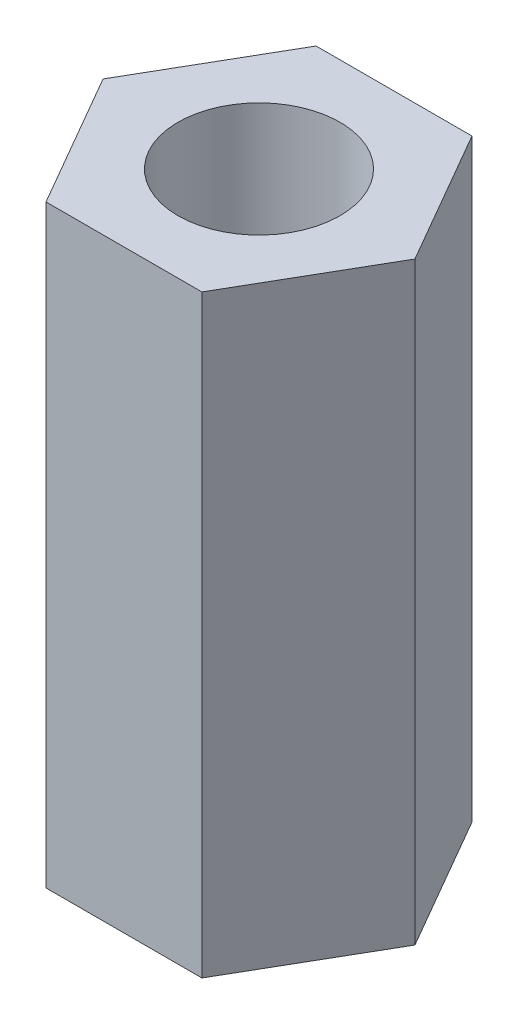
SolidWorks part; units mm, degrees
material "ABS"
ref_plane "Alzado" through (0, 0, 0) normal (0, 0, 1) x (1, 0, 0)
ref_plane "Planta" through (0, 0, 0) normal (0, 1, 0) x (1, 0, 0)
ref_plane "Vista lateral" through (0, 0, 0) normal (1, 0, 0) x (0, 0, -1)
sketch "Croquis1" plane through (0, 0, 0) normal (0, 1, 0) x (1, 0, 0)
  line L1 (1.4434, -2.5) -> (2.8868, 0)
  line L2 (2.8868, 0) -> (1.4434, 2.5)
  line L3 (1.4434, 2.5) -> (-1.4434, 2.5)
  line L4 (-1.4434, 2.5) -> (-2.8868, 0)
  line L5 (-2.8868, 0) -> (-1.4434, -2.5)
  line L6 (-1.4434, -2.5) -> (1.4434, -2.5)
  circle A0 centre (0, 0) radius 2.5 construction
  circle A1 centre (0, 0) radius 1.5
  dimension "D2" = 3
  dimension "D1" = 5
extrude "Saliente-Extruir1" add sketch "Croquis1" along normal mid plane 12
sketch "草图1" plane through (0, 6, 0) normal (0, 1, 0) x (1, 0, 0)
  line L6 (-1.4434, -2.5) -> (1.4434, -2.5)
  line L7 (1.4434, -2.5) -> (2.8868, 0)
  line L8 (2.8868, 0) -> (1.4434, 2.5)
  line L9 (1.4434, 2.5) -> (-1.4434, 2.5)
  line L10 (-1.4434, 2.5) -> (-2.8868, 0)
  line L11 (-2.8868, 0) -> (-1.4434, -2.5)
  line L12 (-1.4434, -2.5) -> (1.4434, -2.5)
  line L13 (1.4434, -2.5) -> (2.8868, 0)
  line L14 (2.8868, 0) -> (1.4434, 2.5)
  line L15 (1.4434, 2.5) -> (-1.4434, 2.5)
  line L16 (-1.4434, 2.5) -> (-2.8868, 0)
  line L17 (-2.8868, 0) -> (-1.4434, -2.5)
  dimension "D1" = 0
extrude "切除-拉伸1" cut sketch "草图1" against normal blind 1
